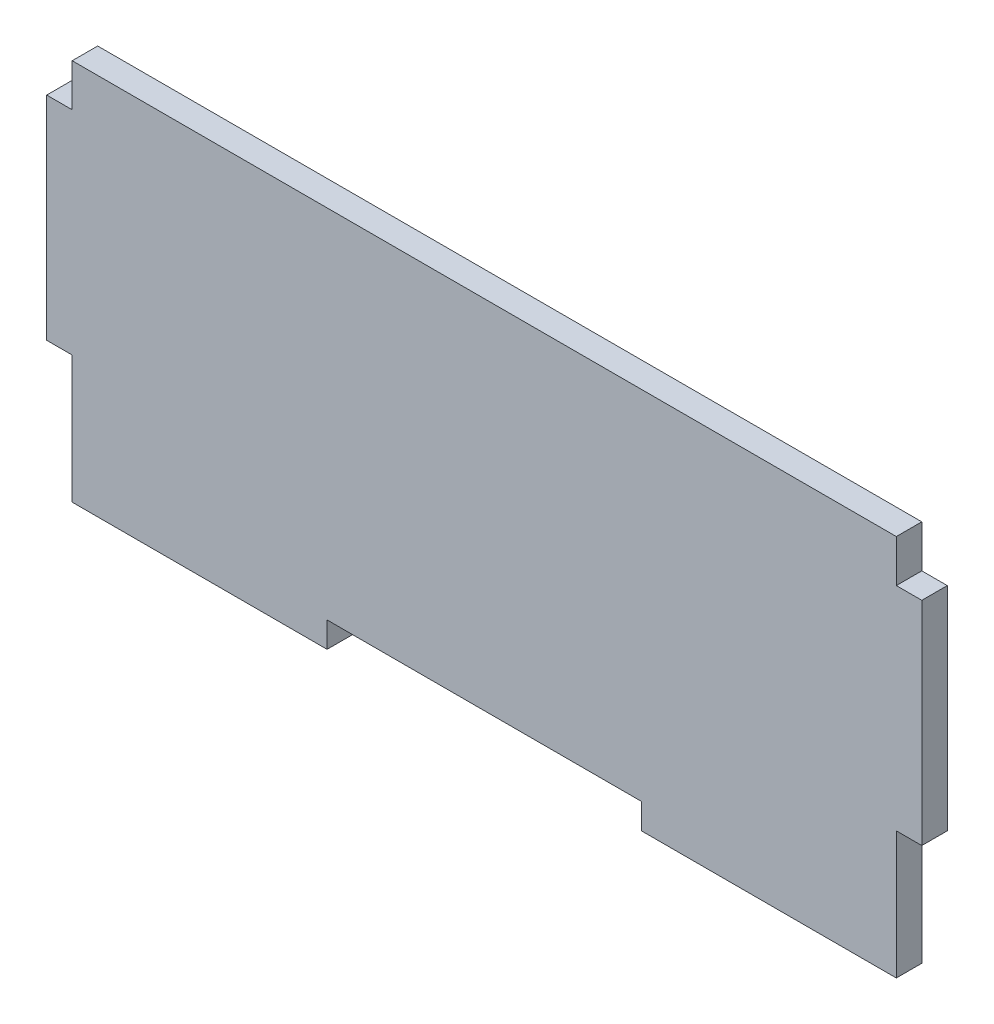
SolidWorks part; units mm, degrees
ref_plane "Plano frontal" through (0, 0, 0) normal (0, 0, 1) x (1, 0, 0)
ref_plane "Plano superior" through (0, 0, 0) normal (0, 1, 0) x (1, 0, 0)
ref_plane "Plano direito" through (0, 0, 0) normal (1, 0, 0) x (0, 0, -1)
sketch "Esboço1" plane through (0, 0, 0) normal (0, 0, 1) x (1, 0, 0)
  line L1 (-51.5, -27.5) -> (51.5, -27.5)
  line L2 (-51.5, -27.5) -> (-51.5, 27.5)
  line L3 (-51.5, 27.5) -> (51.5, 27.5)
  line L4 (51.5, -27.5) -> (51.5, 27.5)
  line L5 (-51.5, -27.5) -> (51.5, 27.5) construction
  line L6 (-51.5, 27.5) -> (51.5, -27.5) construction
  point P0 (0, 0)
  dimension "D1" = 55
  dimension "D2" = 103
extrude "Ressalto-extrusão1" add sketch "Esboço1" along normal blind 3
sketch "Esboço2" plane through (0, 0, 0) normal (0, 0, -1) x (-1, 0, 0)
  line L0 (51.5, -27.5) -> (-51.5, -27.5) construction
  line L1 (-51.5, 27.5) -> (-48.5, 27.5)
  line L2 (-51.5, 27.5) -> (-51.5, -27.5)
  line L3 (-51.5, -27.5) -> (-48.5, -27.5)
  line L4 (-48.5, 27.5) -> (-48.5, -27.5)
  line L5 (-51.5, 12.5) -> (-48.5, 12.5)
  line L6 (51.5, 27.5) -> (48.5, 27.5)
  line L7 (51.5, 27.5) -> (51.5, -27.5)
  line L8 (51.5, -27.5) -> (48.5, -27.5)
  line L9 (48.5, 27.5) -> (48.5, -27.5)
  line L10 (-51.5, -12.5) -> (-48.5, -12.5)
  line L11 (48.5, 12.5) -> (51.5, 12.5)
  line L12 (48.5, -12.5) -> (51.5, -12.5)
  line M8 (-51.5, 27.5) -> (-51.5, -27.5)
  line M9 (-51.5, -27.5) -> (51.5, -27.5)
  line M10 (51.5, -27.5) -> (51.5, 27.5)
  line M11 (51.5, 27.5) -> (-51.5, 27.5)
  dimension "D1" = 3
  dimension "D2" = 15
  dimension "D3" = 15
extrude "Corte-extrusão1" cut sketch "Esboço2" against normal through all contours L5 L4 M8 M11 | L10 L4 M8 M9 | L9 L11 L7 M11 | L12 L9 M9 M10
sketch "Esboço3" plane through (0, 0, 0) normal (0, 0, -1) x (-1, 0, 0)
  line L0 (48.5, -12.5) -> (48.5, -27.5) construction
  line L1 (-48.5, -27.5) -> (48.5, -27.5)
  line L2 (-48.5, -27.5) -> (-48.5, -24.5)
  line L3 (-48.5, -24.5) -> (48.5, -24.5)
  line L4 (48.5, -27.5) -> (48.5, -24.5)
  line L5 (-18.5, -24.5) -> (-18.5, -27.5)
  line L6 (18.5, -24.5) -> (18.5, -27.5)
  dimension "D1" = 3
  dimension "D2" = 30
  dimension "D3" = 30
extrude "Corte-extrusão2" cut sketch "Esboço3" against normal through all contours L6 L3 L5 L1
sketch "Esboço4" plane through (0, 0, 0) normal (0, 0, -1) x (-1, 0, 0)
  line L0 (48.5, 27.5) -> (48.5, 12.5) construction
  line L1 (-48.5, 27.5) -> (48.5, 27.5)
  line L2 (-48.5, 27.5) -> (-48.5, 17.5)
  line L3 (-48.5, 17.5) -> (48.5, 17.5)
  line L4 (48.5, 27.5) -> (48.5, 17.5)
  dimension "D1" = 10
extrude "Corte-extrusão3" cut sketch "Esboço4" against normal blind 10
